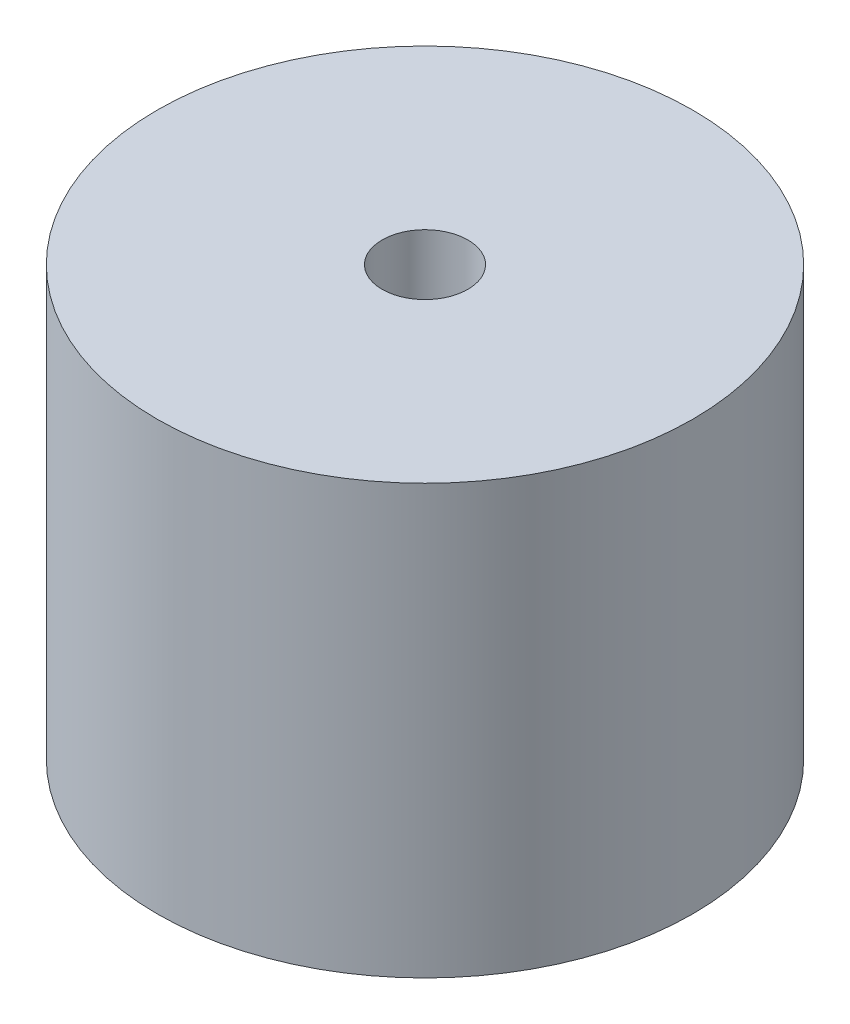
SolidWorks part; units mm, degrees
ref_plane "前视基准面" through (0, 0, 0) normal (0, 0, 1) x (1, 0, 0)
ref_plane "上视基准面" through (0, 0, 0) normal (0, 1, 0) x (1, 0, 0)
ref_plane "右视基准面" through (0, 0, 0) normal (1, 0, 0) x (0, 0, -1)
other "Configuration Table"
sketch "草图1" plane through (0, 0, 0) normal (0, 1, 0) x (1, 0, 0)
  circle A0 centre (0, 0) radius 12.5
  dimension "D1" = 25
extrude "凸台-拉伸1" add sketch "草图1" along normal blind 20
sketch "草图2" plane through (0, 20, 0) normal (0, 1, 0) x (1, 0, 0)
  circle A0 centre (0, 0) radius 2
  dimension "D1" = 4
extrude "切除-拉伸1" cut sketch "草图2" against normal blind 8
